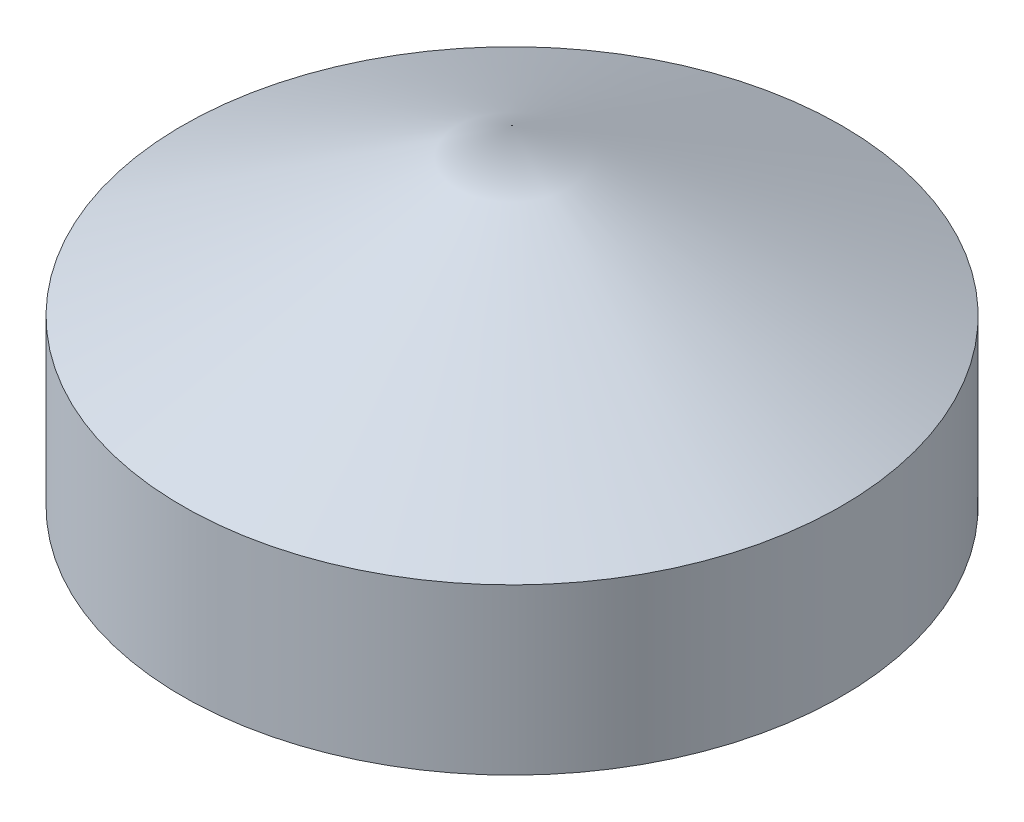
SolidWorks part; units mm, degrees
ref_plane "Front Plane" through (0, 0, 0) normal (0, 0, 1) x (1, 0, 0)
ref_plane "Top Plane" through (0, 0, 0) normal (0, 1, 0) x (1, 0, 0)
ref_plane "Right Plane" through (0, 0, 0) normal (1, 0, 0) x (0, 0, -1)
sketch "Sketch1" plane through (0, 0, 0) normal (0, 0, 1) x (1, 0, 0)
  line L0 (0, 0) -> (0, 18.8275) construction
  line L1 (0, 0) -> (10, 0)
  line L2 (10, 0) -> (10, 5)
  line L3 (10, 5) -> (0, 10)
  line L4 (0, 0) -> (0, 10)
  dimension "D1" = 10
  dimension "D2" = 5
  dimension "D3" = 5
revolve "Revolve1" add sketch "Sketch1" angle 360 about L0
